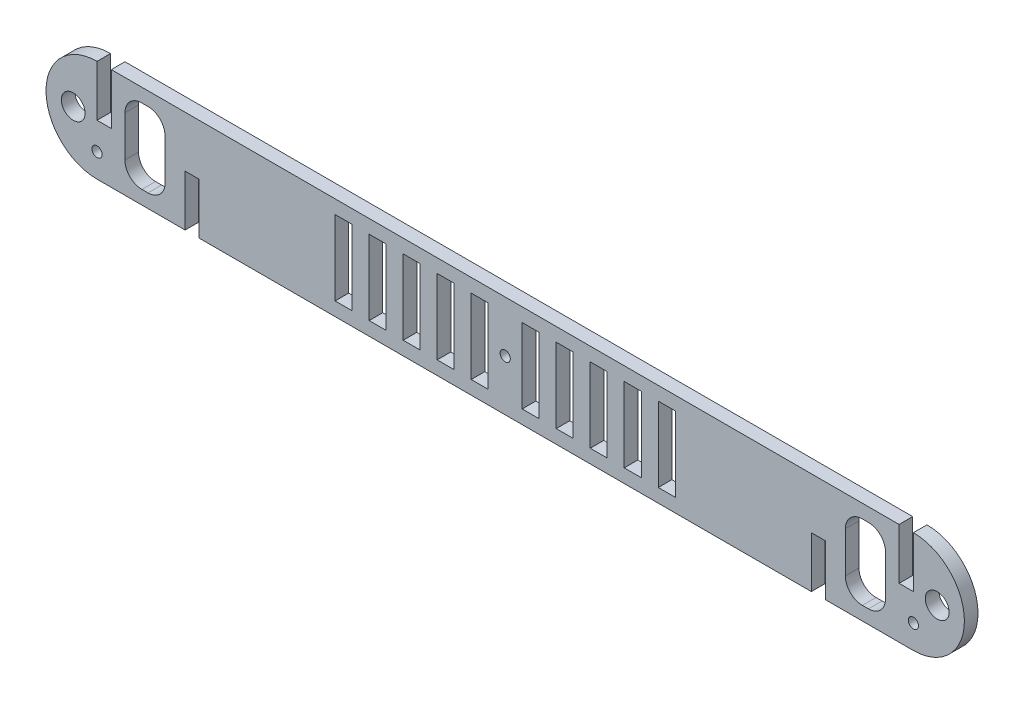
SolidWorks part; units mm, degrees
ref_plane "Front" through (0, 0, 0) normal (0, 0, 1) x (1, 0, 0)
ref_plane "Top" through (0, 0, 0) normal (0, 1, 0) x (1, 0, 0)
ref_plane "Right" through (0, 0, 0) normal (1, 0, 0) x (0, 0, -1)
sketch "Эскиз1" plane through (0, 0, 0) normal (0, 0, 1) x (1, 0, 0)
  line L0 (-120, 15) -> (120, 15)
  line L1 (-120, -15) -> (120, -15)
  line L2 (0, 15) -> (0, -15) construction
  line L3 (-75, 62.9423) -> (0, 62.9423)
  line L4 (-75, 62.9423) -> (-120, -15)
  line L5 (-75, 62.9423) -> (-75, 48.7662) construction
  line L6 (75, 62.9423) -> (120, -15) construction
  line L7 (1.3332, 62.9423) -> (0, 62.9423)
  line L8 (0, 62.9423) -> (0, -15)
  arc A0 (120, -15) -> (120, 15) centre (120, 0) ccw
  arc A1 (-120, -15) -> (-120, 15) centre (-120, 0) cw
  dimension "D2" = 240
  dimension "D3" = 30
  dimension "D1" = 150
  dimension "D4" = 30
extrude "Бобышка-Вытянуть1" add sketch "Эскиз1" along normal mid plane 4 contours A1 L4 L3 L6 A0 L0 | L6 L3 L4 L1 | L1 A0 L0 L8
sketch "Эскиз11" plane through (0, 0, -2) normal (0, 0, -1) x (-1, 0, 0)
  line L0 (120, 15) -> (-120, 15) construction
  line L1 (-120, 15) -> (-115.8, 15)
  line L2 (-120, 15) -> (-120, 0)
  line L3 (-120, 0) -> (-115.8, 0)
  line L4 (-115.8, 15) -> (-115.8, 0)
  line L5 (120, 15) -> (115.8, 15)
  line L6 (120, 15) -> (120, 0)
  line L7 (120, 0) -> (115.8, 0)
  line L8 (115.8, 15) -> (115.8, 0)
  line L9 (-111.8, 11) -> (111.8, 11)
  line L10 (-111.8, 11) -> (-111.8, -11)
  line L11 (-111.8, -11) -> (111.8, -11)
  line L12 (111.8, 11) -> (111.8, -11)
  line L13 (120, -15) -> (-120, -15) construction
  line L14 (-55, 11) -> (-55, -11)
  line L15 (-65, 11) -> (-60, 11)
  line L16 (-65, 11) -> (-65, -11)
  line L17 (-65, -11) -> (-60, -11)
  line L18 (-60, 11) -> (-60, -11)
  line L23 (-55, 11) -> (-50, 11)
  line L24 (-50, 11) -> (-50, -11)
  line L25 (-55, -11) -> (-50, -11)
  line L26 (-45, 11) -> (-45, -11)
  line L27 (-45, 11) -> (-40, 11)
  line L28 (-40, 11) -> (-40, -11)
  line L29 (-45, -11) -> (-40, -11)
  line L30 (-35, 11) -> (-35, -11)
  line L31 (-35, 11) -> (-30, 11)
  line L32 (-30, 11) -> (-30, -11)
  line L33 (-35, -11) -> (-30, -11)
  line L34 (-25, 11) -> (-25, -11)
  line L35 (-25, 11) -> (-20, 11)
  line L36 (-20, 11) -> (-20, -11)
  line L37 (-25, -11) -> (-20, -11)
  line L38 (-15, 11) -> (-15, -11)
  line L39 (-15, 11) -> (-10, 11)
  line L40 (-10, 11) -> (-10, -11)
  line L41 (-15, -11) -> (-10, -11)
  line L42 (-5, 11) -> (-5, -11)
  line L43 (-5, 11) -> (0, 11)
  line L44 (0, 11) -> (0, -11)
  line L45 (-5, -11) -> (0, -11)
  line L46 (15, 11) -> (10, 11)
  line L47 (10, 11) -> (10, -11)
  line L48 (15, -11) -> (10, -11)
  line L49 (15, 11) -> (15, -11)
  line L50 (25, 11) -> (20, 11)
  line L51 (20, 11) -> (20, -11)
  line L52 (25, -11) -> (20, -11)
  line L53 (25, 11) -> (25, -11)
  line L54 (35, 11) -> (30, 11)
  line L55 (30, 11) -> (30, -11)
  line L56 (35, -11) -> (30, -11)
  line L57 (35, 11) -> (35, -11)
  line L58 (45, 11) -> (40, 11)
  line L59 (40, 11) -> (40, -11)
  line L60 (45, -11) -> (40, -11)
  line L61 (45, 11) -> (45, -11)
  line L62 (55, 11) -> (50, 11)
  line L63 (50, 11) -> (50, -11)
  line L64 (55, -11) -> (50, -11)
  line L65 (55, 11) -> (55, -11)
  line L66 (5, 11) -> (5, -11)
  line L67 (65, -11) -> (60, -11)
  line L68 (60, 11) -> (60, -11)
  line L69 (65, 11) -> (60, 11)
  line L70 (65, 11) -> (65, -11)
  circle A0 centre (-127, 0) radius 3.5
  circle A1 centre (127, 0) radius 3.5
  circle A2 centre (0, 0) radius 1.5
  circle A3 centre (-120, -8) radius 1.5
  circle A4 centre (120, -8) radius 1.5
  line M45 (120, 15) -> (-120, 15)
  dimension "D3" = 7
  dimension "D13" = 3
  dimension "D16" = 3
  dimension "D1" = 4.2
  dimension "D2" = 4.2
  dimension "D4" = 7
  dimension "D5" = 7
  dimension "D6" = 4
  dimension "D7" = 4
  dimension "D8" = 4
  dimension "D9" = 4
  dimension "D10" = 5
  dimension "D11" = 60
  dimension "D14" = 5
  dimension "D15" = 8
  dimension "D12" = 7
extrude "Вырез-Вытянуть1" cut sketch "Эскиз11" against normal blind 10 contours L4 L2 L3 M45 | L16 L9 L10 L11 | L9 L18 L11 L14 | L26 L9 L24 L11 | L30 L9 L28 L11 | L34 L9 L32 L11 | L38 L9 L36 L11 | L42 L9 L40 L11 | L9 L66 L11 L47 | L51 L9 L49 L11 | L55 L9 L53 L11 | L59 L9 L57 L11 | L63 L9 L61 L11 | L68 L9 L65 L11 | L9 L70 L11 L12 | L8 L7 L6 M45 | A1 | A0 | A2 | A3 | A4
sketch "Эскиз12" plane through (0, 0, 2) normal (0, 0, 1) x (1, 0, 0)
  line L0 (-111.8, 11) -> (-65, 11) construction
  line L1 (-55, -11) -> (-100, -11)
  line L2 (-55, -11) -> (-55, 11)
  line L3 (-55, 11) -> (-100, 11)
  line L4 (-100, -11) -> (-100, 11)
  dimension "D1" = 45
extrude "Бобышка-Вытянуть2" add sketch "Эскиз12" against normal up to surface (4 mm away)
mirror "Зеркальное отражение1" about plane through (0, 0, 0) normal (1, 0, 0) of "Бобышка-Вытянуть2"
sketch "Эскиз13" plane through (0, 0, 2) normal (0, 0, 1) x (1, 0, 0)
  line L0 (-120, -15) -> (120, -15) construction
  line L1 (-90, -15) -> (-94.1, -15)
  line L2 (-90, -15) -> (-90, 0)
  line L3 (-90, 0) -> (-94.1, 0)
  line L4 (-94.1, -15) -> (-94.1, 0)
  line L5 (-50, -11) -> (-50, 11) construction
  line L6 (-94.1, 0) -> (-100, 0) construction
  line L7 (-100, 11) -> (-100, -11) construction
  dimension "D1" = 4.1
  dimension "D2" = 40
extrude "Вырез-Вытянуть2" cut sketch "Эскиз13" against normal through all
mirror "Зеркальное отражение2" about plane through (0, 0, 0) normal (1, 0, 0) of "Вырез-Вытянуть2"
fillet "Скругление1" radius 5 8 edges at (-100, -11, 0) (-111.8, -11, 0) (-111.8, 11, 0) (-100, 11, 0) (111.8, -11, 0) (100, -11, 0) (100, 11, 0) (111.8, 11, 0)
equation "\"D2@Эскиз1\"=270-30"
